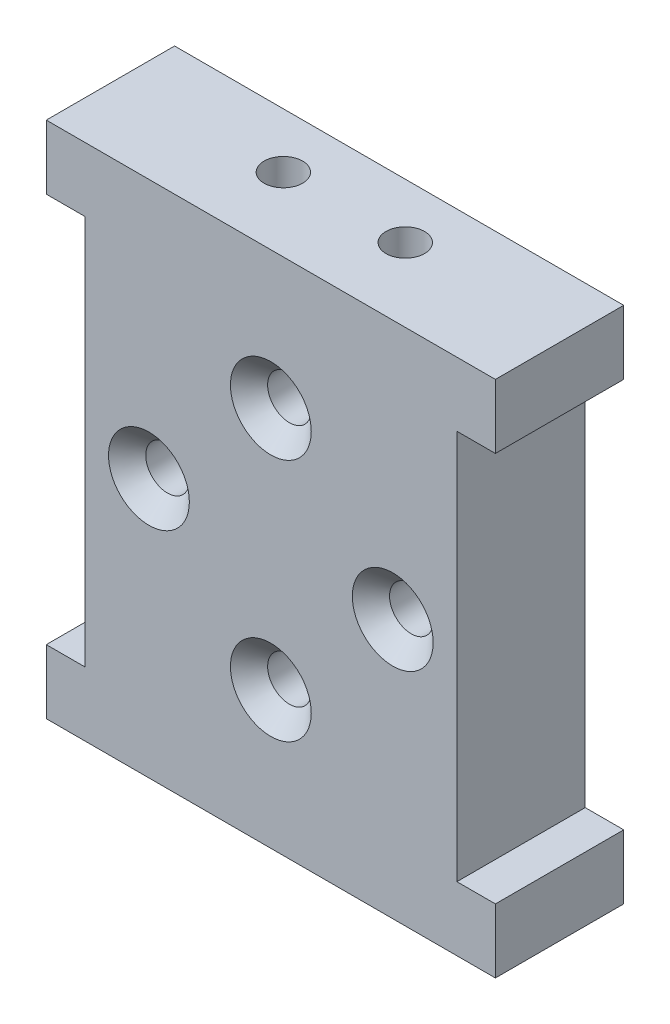
SolidWorks part; units mm, degrees
ref_plane "Front Plane" through (0, 0, 0) normal (0, 0, 1) x (1, 0, 0)
ref_plane "Top Plane" through (0, 0, 0) normal (0, 1, 0) x (1, 0, 0)
ref_plane "Right Plane" through (0, 0, 0) normal (1, 0, 0) x (0, 0, -1)
sketch "Sketch2" plane through (0, 0, 0) normal (0, 0, 1) x (1, 0, 0)
  line L0 (-14.5, 0) -> (14.5, 0) construction
  line L1 (0, -18.1062) -> (0, 18.1062) construction
  line L2 (-14.5, -15.2) -> (-14.5, 15.2)
  line L3 (-14.5, 15.2) -> (-17.5, 15.2)
  line L4 (-17.5, 15.2) -> (-17.5, 20.2)
  line L5 (-17.5, 20.2) -> (17.5, 20.2)
  line L6 (17.5, -15.2) -> (17.5, -20.2)
  line L7 (14.5, -15.2) -> (17.5, -15.2)
  line L8 (-17.5, -20.2) -> (17.5, -20.2)
  line L9 (14.5, -15.2) -> (14.5, 15.2)
  line L10 (14.5, 15.2) -> (17.5, 15.2)
  line L11 (17.5, 15.2) -> (17.5, 20.2)
  line L12 (-17.5, -15.2) -> (-17.5, -20.2)
  line L13 (-14.5, -15.2) -> (-17.5, -15.2)
  line L15 (-9.5, -9.5) -> (9.5, -9.5) construction
  line L16 (-9.5, -9.5) -> (-9.5, 9.5) construction
  line L17 (-9.5, 9.5) -> (9.5, 9.5) construction
  line L18 (9.5, -9.5) -> (9.5, 9.5) construction
  line L19 (-9.5, -9.5) -> (9.5, 9.5) construction
  line L20 (-9.5, 9.5) -> (9.5, -9.5) construction
  point P2 (0, 0)
  point P10 (0, 0)
  point P19 (0, 0)
  dimension "D1" = 29
  dimension "D2" = 15.2
  dimension "D3" = 5
  dimension "D4" = 3
  dimension "D5" = 19
extrude "Boss-Extrude1" add sketch "Sketch2" along normal mid plane 10
sketch "Sketch3" plane through (0, 0, 5) normal (0, 0, 1) x (1, 0, 0)
  line L1 (0, -9.5) -> (9.5, 0) construction
  line L2 (0, -9.5) -> (-9.5, 0) construction
  line L3 (-9.5, 0) -> (0, 9.5) construction
  line L4 (9.5, 0) -> (0, 9.5) construction
  line L5 (0, -9.5) -> (0, 9.5) construction
  line L6 (-9.5, 0) -> (9.5, 0) construction
  line L9 (14.5, -15.2) -> (14.5, 15.2) construction
  point P0 (0, 0)
  point P5 (0, 0)
  dimension "D1" = 19
  dimension "D2" = 19
  dimension "D3" = 45
hole_wizard "CSK for M3 Flat Head Machine Screw1" positions "3DSketch1" profile "Sketch4" countersink size "M3" standard "ANSI Metric"
sketch3d "3DSketch1"
  point P0 (-9.5, 0, 5)
  point P3 (0, 9.5, 5)
  point P6 (9.5, 0, 5)
  point P9 (0, -9.5, 5)
sketch "Sketch4" plane through (-9.5, 0, 5) normal (1, 0, 0) x (0, -1, 0)
  line L0 (0, 0) -> (0, 16.4414)
  line L1 (0, 16.4414) -> (1.7, 15.4)
  line L2 (1.7, 15.4) -> (1.7, 1.45)
  line L3 (1.7, 1.45) -> (3.15, 0)
  line L5 (3.15, 0) -> (0, 0)
  line L6 (-1.7, 1.45) -> (-3.15, 0) construction
  line L10 (0, 16.4414) -> (-1.7, 15.4) construction
  line L11 (0, -6.35) -> (0, 107.95) construction
  dimension "Hole Dia." = 3.4
  dimension "Hole Depth" = 15.4
  dimension "Near C'Sink Dia." = 6.3
  dimension "Near C'Sink Angle" = 90
  dimension "Drill Angle" = 117.02
hole_wizard "Ø3.0mm Dowel Hole1" positions "Sketch8" profile "Sketch9" hole size "Ø3.0" standard "ANSI Metric" end condition up to next
sketch "Sketch8" plane through (0, 20.2, 0) normal (0, 1, 0) x (1, 0, 0)
  line L2 (-7.8, 0.725) -> (-1.7, 0.725) construction
  line L3 (-7.8, -3.55) -> (-7.8, 5) construction
  line L4 (-1.7, 5) -> (-1.7, -3.55) construction
  line L5 (0, 0) -> (0, 4.0012) construction
  line L6 (7.8, 0.725) -> (1.7, 0.725) construction
  point P0 (-4.75, 0.725)
  point P14 (-4.75, 0.725)
  point P21 (4.75, 0.725)
sketch "Sketch9" plane through (-4.75, 20.2, -0.725) normal (1, 0, 0) x (0, 0, 1)
  line L0 (0, 0) -> (0, 40.4)
  line L1 (0, 40.4) -> (1.5, 40.4)
  line L2 (1.5, 40.4) -> (1.5, 0)
  line L5 (1.5, 0) -> (0, 0)
  line L11 (0, -6.35) -> (0, 107.95) construction
  dimension "Thru Hole Dia." = 3
  dimension "Thru Hole Depth" = 40.4
